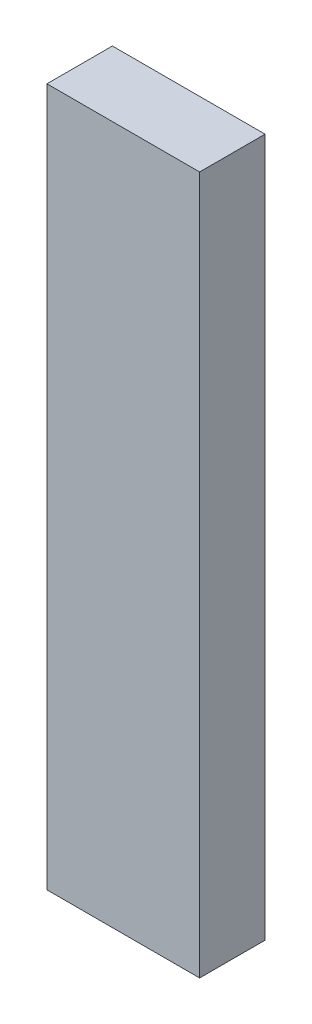
SolidWorks part; units mm, degrees
material "Pine"
ref_plane "Front Plane" through (0, 0, 0) normal (0, 0, 1) x (1, 0, 0)
ref_plane "Top Plane" through (0, 0, 0) normal (0, 1, 0) x (1, 0, 0)
ref_plane "Right Plane" through (0, 0, 0) normal (1, 0, 0) x (0, 0, -1)
sketch "Sketch1" plane through (0, 0, 0) normal (0, 1, 0) x (1, 0, 0)
  line L1 (0, 0) -> (88.9, 0)
  line L2 (0, 0) -> (0, 38.1)
  line L3 (0, 38.1) -> (88.9, 38.1)
  line L4 (88.9, 0) -> (88.9, 38.1)
  dimension "D1" = 88.9
  dimension "D2" = 38.1
extrude "Boss-Extrude1" add sketch "Sketch1" along normal blind 406.4 contours L2 L1 L4 L3
